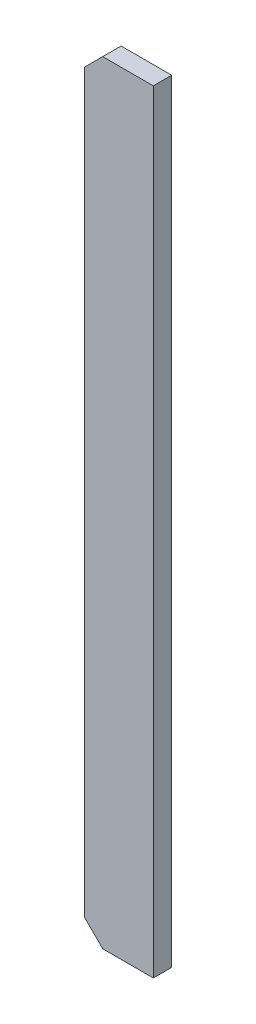
SolidWorks part; units mm, degrees
material "Rubber"
ref_plane "Front Plane" through (0, 0, 0) normal (0, 0, 1) x (1, 0, 0)
ref_plane "Top Plane" through (0, 0, 0) normal (0, 1, 0) x (1, 0, 0)
ref_plane "Right Plane" through (0, 0, 0) normal (1, 0, 0) x (0, 0, -1)
sketch "Sketch1" plane through (0, 0, 0) normal (0, 0, 1) x (1, 0, 0)
  line L0 (-50.8, 520.7) -> (-50.8, 12.7) construction
  line L1 (-50.8, 0) -> (-3.175, 0)
  line L2 (-50.8, 0) -> (-50.8, 533.4)
  line L3 (-50.8, 533.4) -> (-3.175, 533.4)
  line L4 (-3.175, 0) -> (-3.175, 533.4)
  line L5 (-3.175, 533.4) -> (-3.175, 0) construction
  line L6 (-3.175, 533.4) -> (-38.1, 533.4) construction
  dimension "D1" = 533.4
extrude "Boss-Extrude1" add sketch "Sketch1" along normal blind 12.7
chamfer "Chamfer1" distance 12.7 angle 45 2 edges at (-50.8, 533.4, 6.35) (-50.8, 0, 6.35)
sketch "Sketch2" [suppressed] plane through (0, 0, 12.7) normal (0, 0, 1) x (1, 0, 0)
  line L0 (-38.1, 520.7) -> (-25.4, 533.4) construction
  line L1 (-25.4, 0) -> (-38.1, 12.7) construction
  line L2 (-38.1, 520.7) -> (-38.1, 12.7) construction
  line L3 (-38.1, 520.7) -> (-25.4, 533.4)
  line L4 (-25.4, 0) -> (-38.1, 12.7)
  line L5 (-38.1, 520.7) -> (-38.1, 12.7)
  line L6 (-25.4, 533.4) -> (-50.8, 533.4)
  line L7 (-50.8, 533.4) -> (-50.8, 0)
  line L8 (-50.8, 0) -> (-25.4, 0)
  line L9 (-50.8, 520.7) -> (-50.8, 12.7) construction
extrude "Cut-Extrude1" [suppressed] cut sketch "Sketch2" against normal through all
